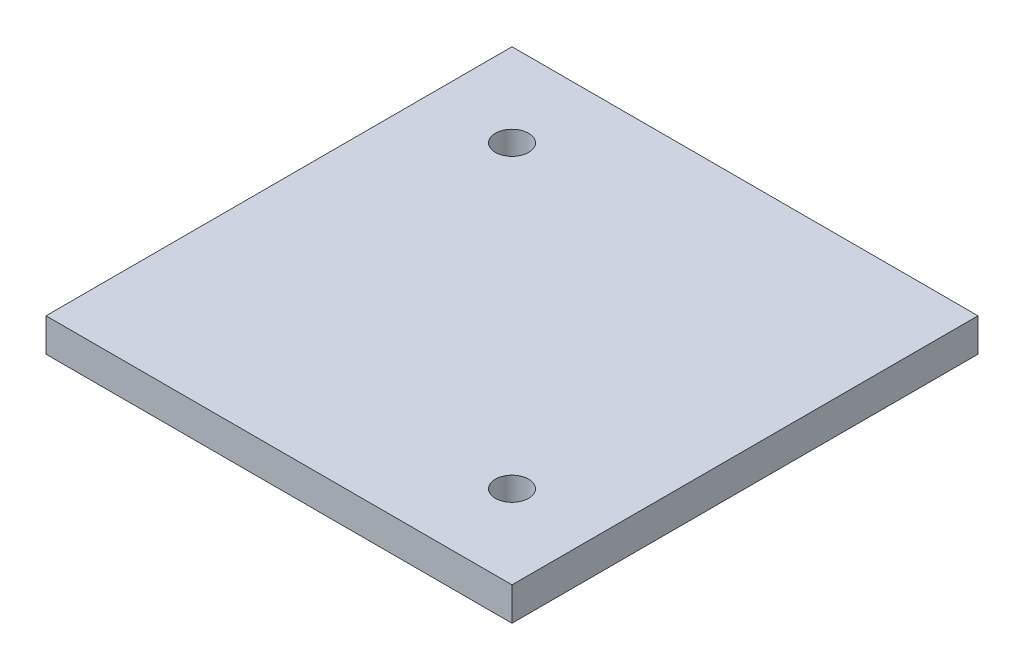
SolidWorks part; units mm, degrees
ref_plane "Front Plane" through (0, 0, 0) normal (0, 0, 1) x (1, 0, 0)
ref_plane "Top Plane" through (0, 0, 0) normal (0, 1, 0) x (1, 0, 0)
ref_plane "Right Plane" through (0, 0, 0) normal (1, 0, 0) x (0, 0, -1)
sketch "Sketch1" plane through (0, 0, 0) normal (0, 1, 0) x (1, 0, 0)
  line L1 (0, 0) -> (44.45, 0)
  line L2 (0, 0) -> (0, 44.45)
  line L3 (0, 44.45) -> (44.45, 44.45)
  line L4 (44.45, 0) -> (44.45, 44.45)
  circle A0 centre (7.9375, 36.5125) radius 1.5875
  circle A1 centre (36.5125, 7.9375) radius 1.5875
  dimension "D6" = 3.175
  dimension "D1" = 44.45
  dimension "D2" = 7.9375
  dimension "D3" = 7.9375
  dimension "D4" = 7.9375
  dimension "D5" = 7.9375
  dimension "D7" = 36.5125
extrude "Boss-Extrude1" add sketch "Sketch1" along normal blind 3.175
equation "\"LowerCornerBlockWidth\"= \"LowerRailWidth\" - \"RailThickness\" * 2'Room for left front stepper"
equation "\"D1@Sketch1\"=\"LowerCornerBlockWidth\""
equation "\"LowerRailWidth\"= 2.00in"
equation "\"RailThickness\"= .125in'Spec"
equation "\"HoleOffsetFromEdge\"= \"RailThickness\" * 2.5"
equation "\"D4@Sketch1\"=\"HoleOffsetFromEdge\""
equation "\"D2@Sketch1\"=\"HoleOffsetFromEdge\""
equation "\"D5@Sketch1\"=\"HoleOffsetFromEdge\""
equation "\"D3@Sketch1\"=\"HoleOffsetFromEdge\""
equation "\"FasteningHoleDiameter\"= .125in"
equation "\"D6@Sketch1\"=\"FasteningHoleDiameter\""
equation "\"D1@Boss-Extrude1\"=\"RailThickness\""
